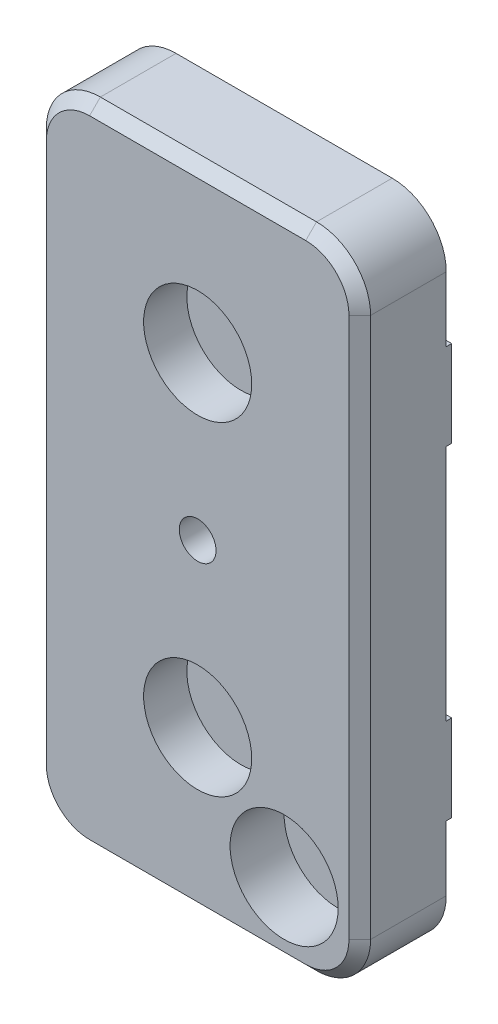
SolidWorks part; units mm, degrees
material "3D printed plastic"
ref_plane "Front Plane" through (0, 0, 0) normal (0, 0, 1) x (1, 0, 0)
ref_plane "Top Plane" through (0, 0, 0) normal (0, 1, 0) x (1, 0, 0)
ref_plane "Right Plane" through (0, 0, 0) normal (1, 0, 0) x (0, 0, -1)
sketch "Sketch1" plane through (0, 0, 0) normal (1, 0, 0) x (0, 0, -1)
  line L0 (8, -19) -> (8, -30)
  line L1 (8, -11) -> (8.5, -11)
  line L2 (8, -11) -> (8, -19) construction
  line L3 (8, -19) -> (8.5, -19)
  line L4 (8.5, -11) -> (8.5, -19)
  line L5 (8, 0) -> (0, 0) construction
  line L6 (8, 11) -> (8, -11)
  line L7 (8, -30) -> (0, -30)
  line L8 (0, 30) -> (0, -30)
  line L9 (8, 11) -> (8, 19) construction
  line L10 (8, 30) -> (0, 30)
  line L11 (8.5, 11) -> (8.5, 19)
  line L12 (8, 19) -> (8.5, 19)
  line L13 (8, 11) -> (8.5, 11)
  line L14 (8, 19) -> (8, 30)
  dimension "D1" = 0.5
  dimension "D2" = 8
  dimension "D3" = 30
  dimension "D4" = 8
  dimension "D5" = 60
extrude "Boss-Extrude1" add sketch "Sketch1" along normal mid plane 30
hole_wizard "M4 Clearance Hole1" positions "Sketch3" profile "Sketch2" hole size "M4" standard "DIN"
sketch "Sketch3" plane through (0, 0, 0) normal (0, 0, 1) x (1, 0, 0)
  line L0 (0, -15) -> (0, 15) construction
  point P0 (0, -15)
  point P2 (0, 15)
  dimension "D1" = 30
sketch "Sketch2" plane through (0, -15, 0) normal (1, 0, 0) x (0, -1, 0)
  line L0 (0, 0) -> (0, 17.3519)
  line L1 (0, 17.3519) -> (2.25, 16)
  line L2 (2.25, 16) -> (2.25, 0)
  line L5 (2.25, 0) -> (0, 0)
  line L10 (0, 17.3519) -> (-2.25, 16) construction
  line L11 (0, -6.35) -> (0, 107.95) construction
  dimension "Hole Dia." = 4.5
  dimension "Hole Depth" = 16
  dimension "Drill Angle" = 118
hole_wizard "CBORE for M3 Hex Socket Head Cap Screw1" positions "Sketch5" profile "Sketch4" counterbore size "M3" standard "DIN" end condition through all
sketch "Sketch5" plane through (0, 0, -8.5) normal (0, 0, -1) x (-1, 0, 0)
  point P0 (0, 0)
sketch "Sketch4" plane through (0, 0, -8.5) normal (1, 0, 0) x (0, 1, 0)
  line L0 (0, 0) -> (0, 8.5)
  line L1 (0, 8.5) -> (1.7, 8.5)
  line L3 (1.7, 8.5) -> (1.7, 6)
  line L4 (1.7, 6) -> (3.25, 6)
  line L5 (3.25, 6) -> (3.25, 0)
  line L7 (3.25, 0) -> (0, 0)
  line L11 (0, -6.35) -> (0, 107.95) construction
  dimension "Thru Hole Dia." = 3.4
  dimension "Thru Hole Depth" = 8.5
  dimension "C'Bore Dia." = 6.5
  dimension "C'Bore Depth" = 6
fillet "Fillet1" radius 5 4 edges at (15, -30, -4) (-15, -30, -4) (-15, 30, -4) (15, 30, -4)
chamfer "Chamfer1" distance 1 angle 45 8 edges at (0, -30, 0) (13.5355, -28.5355, 0) (-13.5355, -28.5355, 0) (15, 0, 0) (-15, 0, 0) (13.5355, 28.5355, 0) (-13.5355, 28.5355, 0) (0, 30, 0)
sketch "Sketch6" plane through (0, 0, 0) normal (0, 0, 1) x (1, 0, 0)
  line L0 (10, -30) -> (-10, -30) construction
  line L1 (15, 25) -> (15, -25) construction
  circle A0 centre (8, -23) radius 5
  dimension "D1" = 10
  dimension "D2" = 7
  dimension "D3" = 7
extrude "Cut-Extrude1" cut sketch "Sketch6" against normal blind 5
sketch "Sketch7" plane through (0, 0, 0) normal (0, 0, 1) x (1, 0, 0)
  circle A0 centre (0, 15) radius 5
  circle A1 centre (0, -15) radius 5
  dimension "D1" = 10
extrude "Cut-Extrude2" cut sketch "Sketch7" against normal blind 4
sketch "Sketch8" plane through (0, 0, -4) normal (0, 0, 1) x (1, 0, 0)
  circle A0 centre (0, 15) radius 2.25
  circle A1 centre (0, -15) radius 2.25
  circle A2 centre (0, -15) radius 2.25 construction
  circle A3 centre (0, 15) radius 2.25 construction
extrude "Boss-Extrude2" add sketch "Sketch8" against normal blind 0.4
